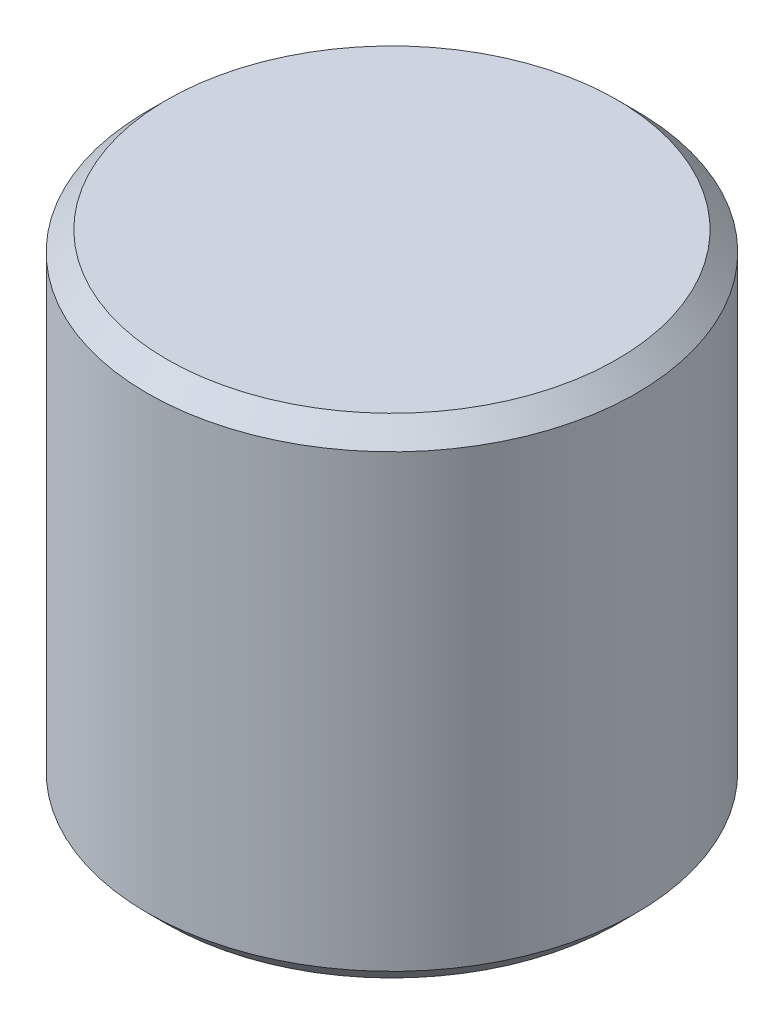
SolidWorks part; units mm, degrees
ref_plane "Front Plane" through (0, 0, 0) normal (0, 0, 1) x (1, 0, 0)
ref_plane "Top Plane" through (0, 0, 0) normal (0, 1, 0) x (1, 0, 0)
ref_plane "Right Plane" through (0, 0, 0) normal (1, 0, 0) x (0, 0, -1)
sketch "Sketch1" plane through (0, 0, 0) normal (0, 1, 0) x (1, 0, 0)
  circle A0 centre (0, 0) radius 7.9375
  dimension "D1" = 15.875
extrude "Boss-Extrude1" add sketch "Sketch1" along normal blind 15.875
chamfer "Chamfer1" distance 0.635 angle 45 2 edges at (0, 0, 7.9375) (0, 15.875, 7.9375)
